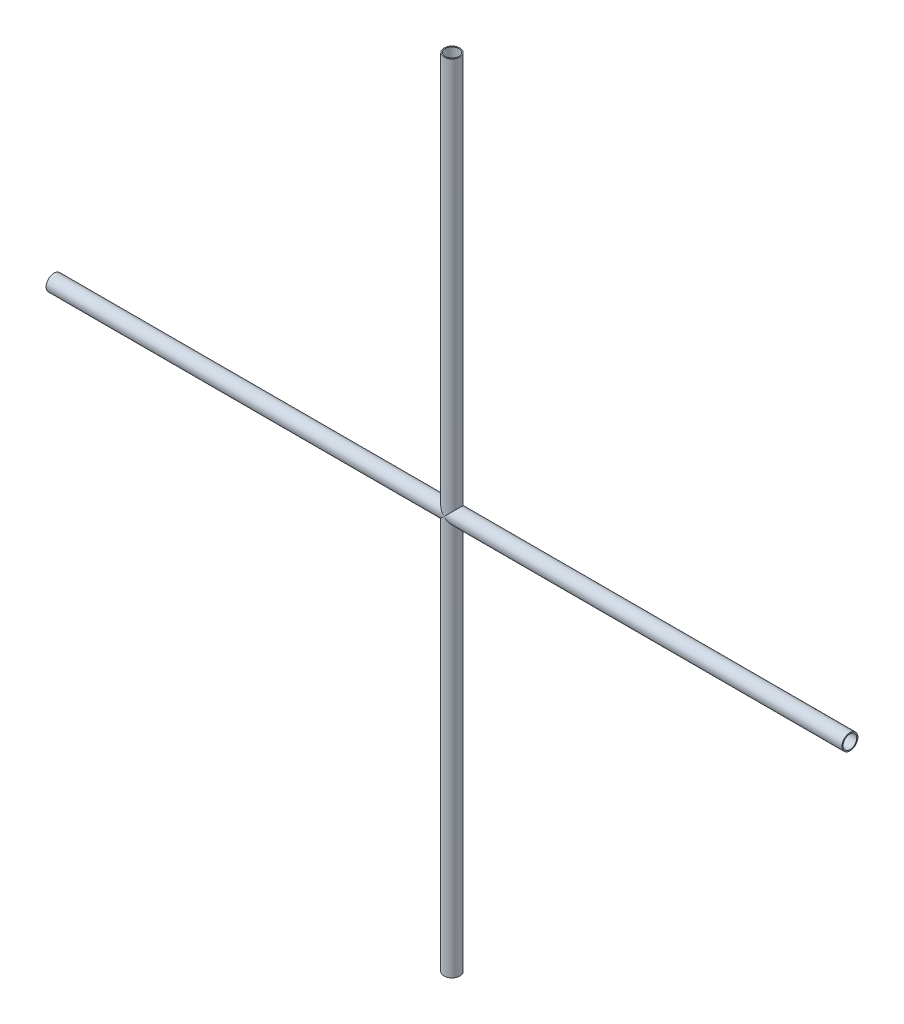
SolidWorks part; units mm, degrees
material "Hexcel AS4C (3000 Filaments)"
ref_plane "Front Plane" through (0, 0, 0) normal (0, 0, 1) x (1, 0, 0)
ref_plane "Top Plane" through (0, 0, 0) normal (0, 1, 0) x (1, 0, 0)
ref_plane "Right Plane" through (0, 0, 0) normal (1, 0, 0) x (0, 0, -1)
sketch "Sketch1" plane through (0, 0, 0) normal (0, 1, 0) x (1, 0, 0)
  circle A0 centre (0, 0) radius 3
  circle A1 centre (0, 0) radius 2.575
  dimension "D1" = 6
  dimension "D2" = 5.15
extrude "Boss-Extrude1" add sketch "Sketch1" along normal mid plane 300
sketch "Sketch2" plane through (0, 0, 0) normal (1, 0, 0) x (0, 0, -1)
  circle A0 centre (0, 0) radius 3
  circle A1 centre (0, 0) radius 2.575
  dimension "D1" = 6
  dimension "D2" = 5.15
extrude "Boss-Extrude2" add sketch "Sketch2" along normal mid plane 300
